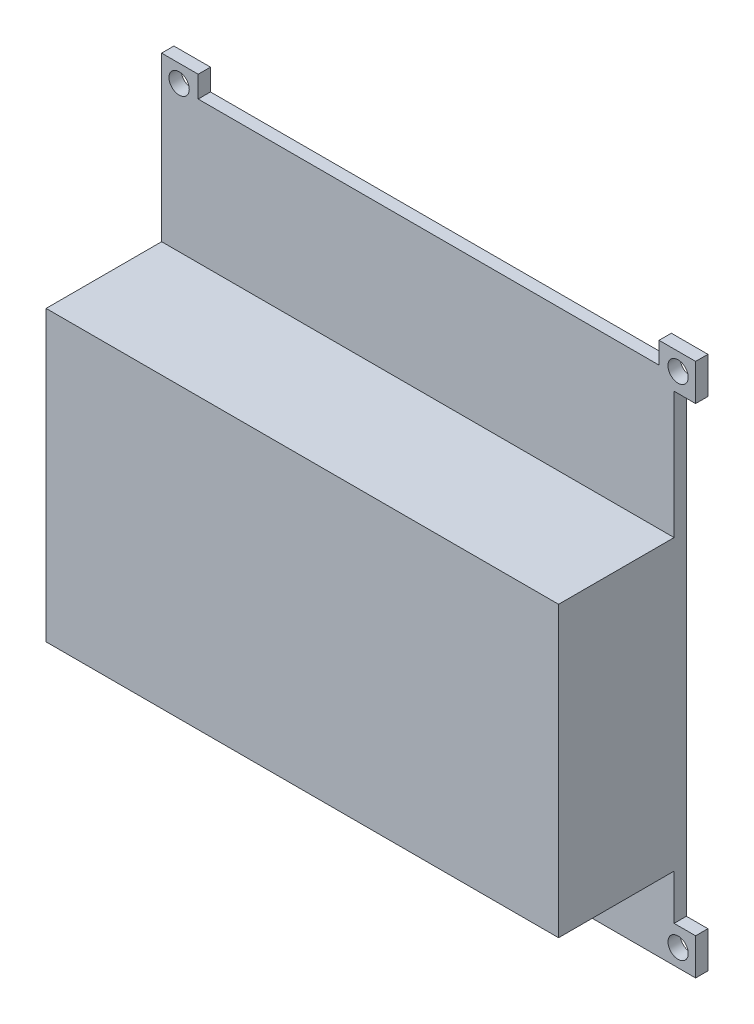
SolidWorks part; units mm, degrees
ref_plane "Front Plane" through (0, 0, 0) normal (1, 0, 0) x (0, 1, 0)
ref_plane "Top Plane" through (0, 0, 0) normal (0, 0, 1) x (0, 1, 0)
ref_plane "Right Plane" through (0, 0, 0) normal (0, 1, 0) x (-1, 0, 0)
sketch "Sketch1" plane through (0, 0, 0) normal (0, 0, 1) x (0, 1, 0)
  line L1 (0, 0) -> (86.9, 0)
  line L2 (0, 0) -> (0, 86.9)
  line L3 (0, 86.9) -> (86.9, 86.9)
  line L4 (86.9, 0) -> (86.9, 86.9)
  dimension "D1" = 86.9
  dimension "D2" = 86.9
extrude "Boss-Extrude1" add sketch "Sketch1" along normal blind 2 contours L3 L4 L1 L2
sketch "Sketch2" plane through (0, 0, 2) normal (0, 0, 1) x (1, 0, 0)
  line L0 (0, 0) -> (-86.9, 0) construction
  line L1 (-84.05, 84.05) -> (-2.85, 84.05) construction
  line L2 (-84.05, 84.05) -> (-84.05, 2.85) construction
  line L3 (-84.05, 2.85) -> (-2.85, 2.85) construction
  line L4 (-2.85, 84.05) -> (-2.85, 2.85) construction
  line L5 (0, 0) -> (0, 86.9) construction
  circle A0 centre (-84.05, 2.85) radius 1.65
  circle A1 centre (-2.85, 2.85) radius 1.65
  circle A2 centre (-2.85, 84.05) radius 1.65
  circle A3 centre (-84.05, 84.05) radius 1.65
  dimension "D3" = 3.3
  dimension "D1" = 81.2
  dimension "D2" = 81.2
  dimension "D4" = 2.85
  dimension "D5" = 2.85
extrude "Cut-Extrude3" cut sketch "Sketch2" against normal through all
sketch "Sketch5" plane through (0, 0, 2) normal (0, 0, 1) x (1, 0, 0)
  line L0 (-86.9, 0) -> (-86.9, 86.9) construction
  line L1 (-86.9, 60.32) -> (0, 60.32)
  line L2 (-86.9, 60.32) -> (-86.9, 13.32)
  line L3 (-86.9, 13.32) -> (0, 13.32)
  line L4 (0, 60.32) -> (0, 13.32)
  line L5 (0, 0) -> (0, 86.9) construction
  line L6 (0, 0) -> (-86.9, 0) construction
  dimension "D1" = 47
  dimension "D2" = 13.32
extrude "Boss-Extrude3" add sketch "Sketch5" along normal blind 18.8 contours L2 L3 L4 L1
sketch "Sketch6" plane through (0, 13.32, 0) normal (0, -1, 0) x (1, 0, 0)
  line L0 (-86.9, 2) -> (0, 2) construction
  line L1 (-86.9, 18.8) -> (-13.12, 18.8)
  line L2 (-86.9, 18.8) -> (-86.9, 2)
  line L3 (-86.9, 2) -> (-13.12, 2)
  line L4 (-13.12, 18.8) -> (-13.12, 2)
  line L6 (-86.9, 20.8) -> (-86.9, 2) construction
  dimension "D1" = 16.8
  dimension "D2" = 73.78
extrude "Cut-Extrude5" cut sketch "Sketch6" against normal blind 43 from offset 2 contours L2 L3 L4 L1 offset against normal yes
ref_plane "Plane1" through (0, 0, 1) normal (0, 0, -1) x (0, 1, 0)
sketch "Sketch8" plane through (0, 0, 2) normal (0, 0, 1) x (1, 0, 0)
  line L0 (0, 60.32) -> (0, 86.9) construction
  line L1 (0, 80.95) -> (-3.5, 80.95)
  line L2 (0, 80.95) -> (0, 5.95)
  line L3 (0, 5.95) -> (-3.5, 5.95)
  line L4 (-3.5, 80.95) -> (-3.5, 5.95)
  line L5 (0, 86.9) -> (0, 0) construction
  line L6 (0, 86.9) -> (-86.9, 0) construction
  line L7 (0, 0) -> (-86.9, 0) construction
  line L8 (-80.95, 86.9) -> (-80.95, 83.4)
  line L9 (-5.95, 83.4) -> (-80.95, 83.4)
  line L10 (-5.95, 86.9) -> (-5.95, 83.4)
  line L11 (-5.95, 86.9) -> (-80.95, 86.9)
  point P6 (0, 43.45)
  point P10 (0, 43.45)
  dimension "D1" = 3.5
  dimension "D2" = 75
extrude "Cut-Extrude7" cut sketch "Sketch8" against normal through all both and the other way through all
